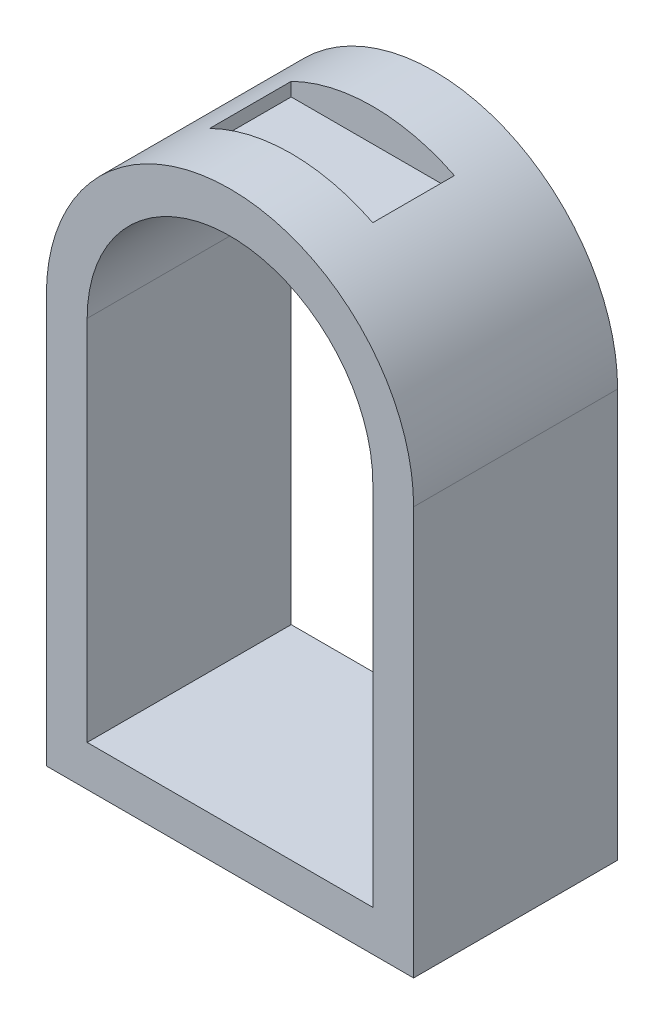
SolidWorks part; units mm, degrees
ref_plane "Front Plane" through (0, 0, 0) normal (0, 0, 1) x (1, 0, 0)
ref_plane "Top Plane" through (0, 0, 0) normal (0, 1, 0) x (1, 0, 0)
ref_plane "Right Plane" through (0, 0, 0) normal (1, 0, 0) x (0, 0, -1)
sketch "Sketch1" plane through (0, 0, 0) normal (0, 0, 1) x (1, 0, 0)
  line L0 (-25.4, -25.4) -> (-25.4, 228.6)
  line L1 (0, 0) -> (177.8, 0)
  line L2 (0, 0) -> (0, 228.6)
  line L3 (0, 228.6) -> (177.8, 228.6) construction
  line L4 (177.8, 0) -> (177.8, 228.6)
  line L5 (203.2, -25.4) -> (203.2, 228.6)
  line L6 (-25.4, -25.4) -> (203.2, -25.4)
  arc A0 (0, 228.6) -> (177.8, 228.6) centre (88.9, 228.6) cw
  arc A1 (-25.4, 228.6) -> (203.2, 228.6) centre (88.9, 228.6) cw
  dimension "D3" = 25.4
  dimension "D1" = 177.8
  dimension "D2" = 228.6
extrude "Boss-Extrude1" add sketch "Sketch1" along normal blind 127 from offset 0
ref_plane "Plane1" through (0, 342.9, 0) normal (0, 1, 0) x (1, 0, 0)
sketch "Sketch2" plane through (0, 342.9, 0) normal (0, 1, 0) x (1, 0, 0)
  line L0 (88.9, 0) -> (88.9, -127) construction
  line L1 (38.1, -38.1) -> (139.7, -38.1)
  line L2 (38.1, -38.1) -> (38.1, -88.9)
  line L3 (38.1, -88.9) -> (139.7, -88.9)
  line L4 (139.7, -38.1) -> (139.7, -88.9)
  line L5 (203.2, 0) -> (-25.4, 0) construction
  line L6 (-25.4, -127) -> (203.2, -127) construction
  line L7 (-25.4, -63.5) -> (203.2, -63.5) construction
  line L8 (-25.4, -127) -> (-25.4, 0) construction
  line L9 (203.2, -127) -> (203.2, 0) construction
  point P10 (88.9, -38.1)
  point P17 (38.1, -63.5)
  dimension "D1" = 101.6
  dimension "D2" = 50.8
extrude "Cut-Extrude1" cut sketch "Sketch2" against normal blind 20.32 and the other way through all
